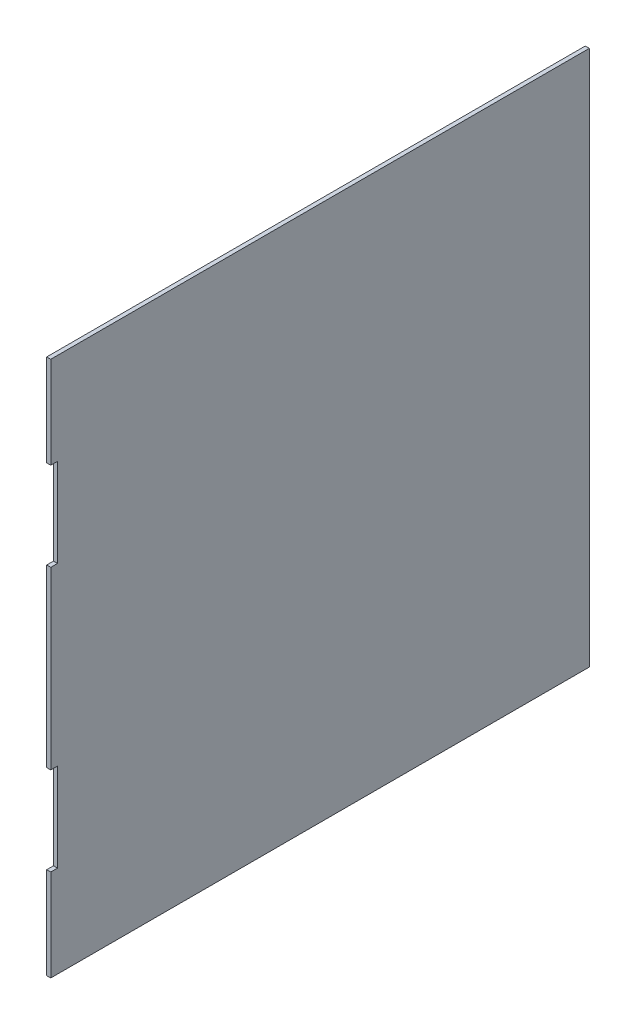
SolidWorks part; units mm, degrees
ref_plane "前基準面" through (0, 0, 0) normal (0, 0, 1) x (1, 0, 0)
ref_plane "上基準面" through (0, 0, 0) normal (0, 1, 0) x (1, 0, 0)
ref_plane "右基準面" through (0, 0, 0) normal (1, 0, 0) x (0, 0, -1)
sketch "草圖1" plane through (0, 0, 0) normal (1, 0, 0) x (0, 0, -1)
  line L1 (-199.5, -198.5) -> (199.5, -198.5)
  line L2 (-199.5, -198.5) -> (-199.5, 198.5)
  line L3 (-199.5, 198.5) -> (199.5, 198.5)
  line L4 (199.5, -198.5) -> (199.5, 198.5)
  line L5 (-199.5, -198.5) -> (199.5, 198.5) construction
  line L6 (-199.5, 198.5) -> (199.5, -198.5) construction
  point P0 (0, 0)
  dimension "D1" = 399
  dimension "D2" = 397
extrude "填料-伸長1" add sketch "草圖1" along normal blind 3
sketch "草圖2" plane through (3, 0, 0) normal (1, 0, 0) x (0, 0, -1)
  line L0 (-199.5, 198.5) -> (-199.5, -198.5) construction
  line L1 (-199.5, 130.5) -> (-194.5, 130.5)
  line L2 (-199.5, 130.5) -> (-199.5, 65)
  line L3 (-199.5, 65) -> (-194.5, 65)
  line L4 (-194.5, 130.5) -> (-194.5, 65)
  line L5 (1.65, 0) -> (-1.65, 0) construction
  line L10 (-194.5, -130.5) -> (-194.5, -65)
  line L11 (-199.5, -65) -> (-194.5, -65)
  line L12 (-199.5, -130.5) -> (-199.5, -65)
  line L13 (-199.5, -130.5) -> (-194.5, -130.5)
  dimension "D1" = 65.5
  dimension "D2" = 5
  dimension "D3" = 65
extrude "除料-伸長1" cut sketch "草圖2" against normal blind 3
equation "\"ˇ\"=10"
